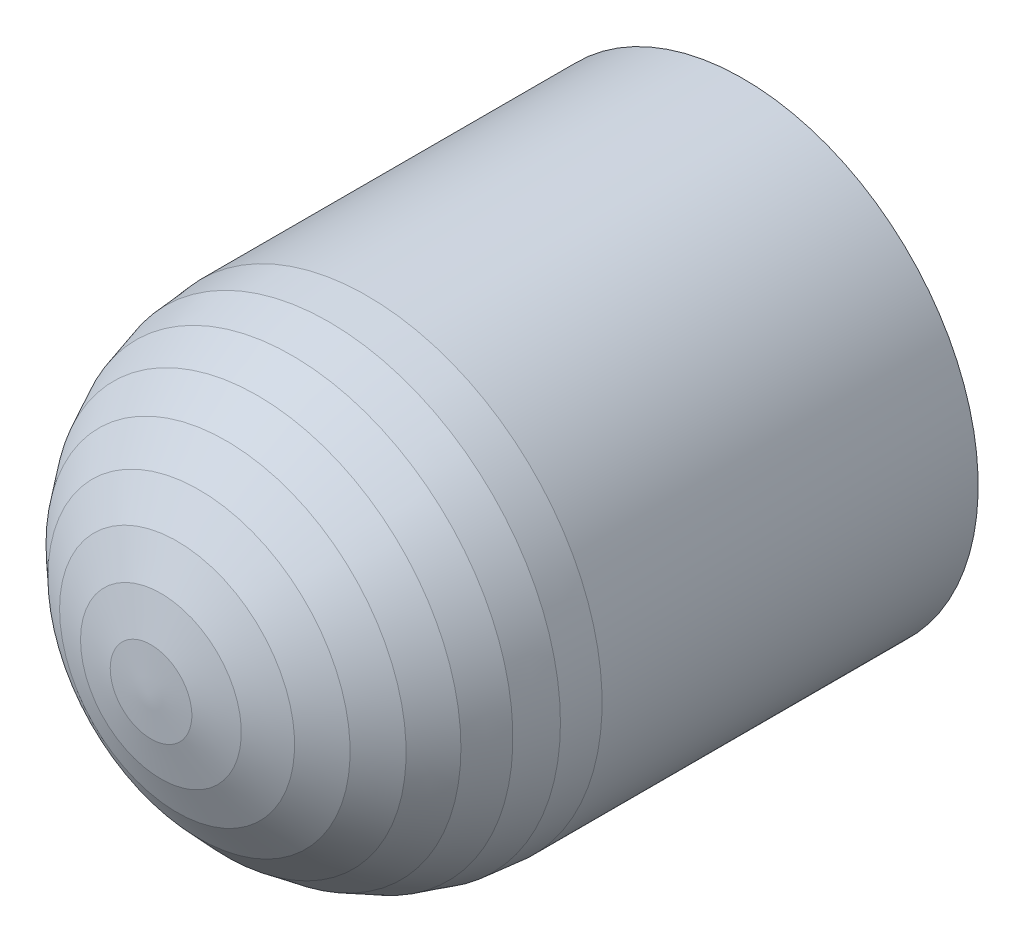
SolidWorks part; units mm, degrees
ref_plane "Front Plane" through (0, 0, 0) normal (1, 0, 0) x (0, 1, 0)
ref_plane "Top Plane" through (0, 0, 0) normal (0, 0, 1) x (0, 1, 0)
ref_plane "Right Plane" through (0, 0, 0) normal (0, 1, 0) x (-1, 0, 0)
sketch "Sketch1" plane through (0, 0, 0) normal (0, 1, 0) x (-1, 0, 0)
  line L0 (0, 0) -> (-75, 0)
  line L1 (-75, 0) -> (-75, 120)
  line L2 (-75, 120) -> (-73.8606, 132.1554)
  line L3 (-73.8606, 132.1554) -> (-70.4769, 143.9414)
  line L4 (-70.4769, 143.9414) -> (-64.9519, 155)
  line L5 (-64.9519, 155) -> (-57.4533, 164.9951)
  line L6 (-57.4533, 164.9951) -> (-48.2091, 173.6231)
  line L7 (-48.2091, 173.6231) -> (-37.5, 180.6218)
  line L8 (-37.5, 180.6218) -> (-25.6515, 185.7785)
  line L9 (-25.6515, 185.7785) -> (-13.0236, 188.9365)
  line L10 (-13.0236, 188.9365) -> (0, 190)
  line L11 (0, 190) -> (0, 0)
  line L12 (0, -10) -> (0, 200) construction
revolve "Revolve1" add sketch "Sketch1" angle 360 about L12
